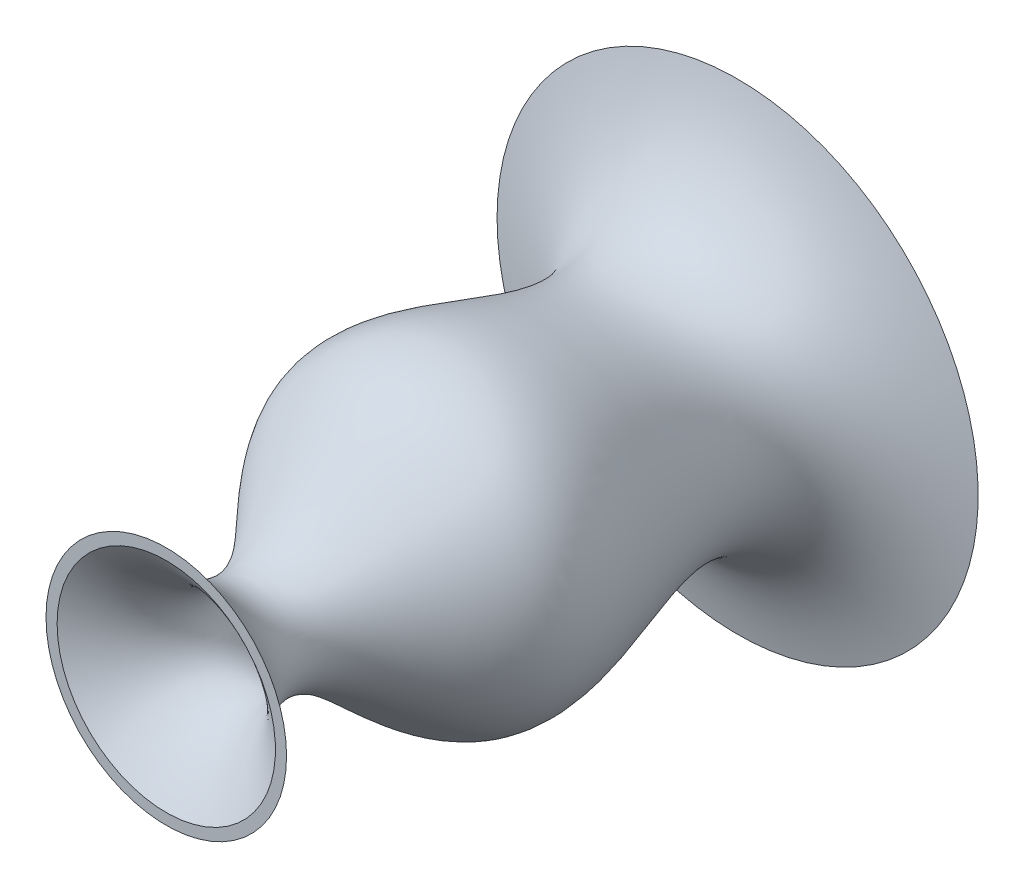
SolidWorks part; units mm, degrees
ref_plane "Front Plane" through (0, 0, 0) normal (1, 0, 0) x (0, 1, 0)
ref_plane "Top Plane" through (0, 0, 0) normal (0, 0, 1) x (0, 1, 0)
ref_plane "Right Plane" through (0, 0, 0) normal (0, 1, 0) x (-1, 0, 0)
sketch "Sketch1" plane through (0, 0, 0) normal (1, 0, 0) x (0, 1, 0)
  line L0 (0, 0) -> (0, 241.3)
  line L1 (0, 241.3) -> (50.8, 241.3)
  line L2 (0, 0) -> (101.6, 0)
  spline S0 degree 3 poles (50.8, 241.3) (-17.1723, 198.7081) (140.9896, 144.4488) (-0.615, 24.6496) (101.6, 0) knots 0 0 0 0 0.431375 1 1 1 1
  point P6 (16.9397, 208.816)
  dimension "D1" = 241.3
  dimension "D2" = 25.4
  dimension "D3" = 63.5
  dimension "D4" = 50.8
  dimension "D5" = 50.8
  dimension "D6" = 101.6
  dimension "D7" = 50.8
  dimension "D8" = 101.6
  dimension "D9" = 177.8
revolve "Revolve1" add sketch "Sketch1" angle 360 about L0
shell "Shell1" thickness 2.54
